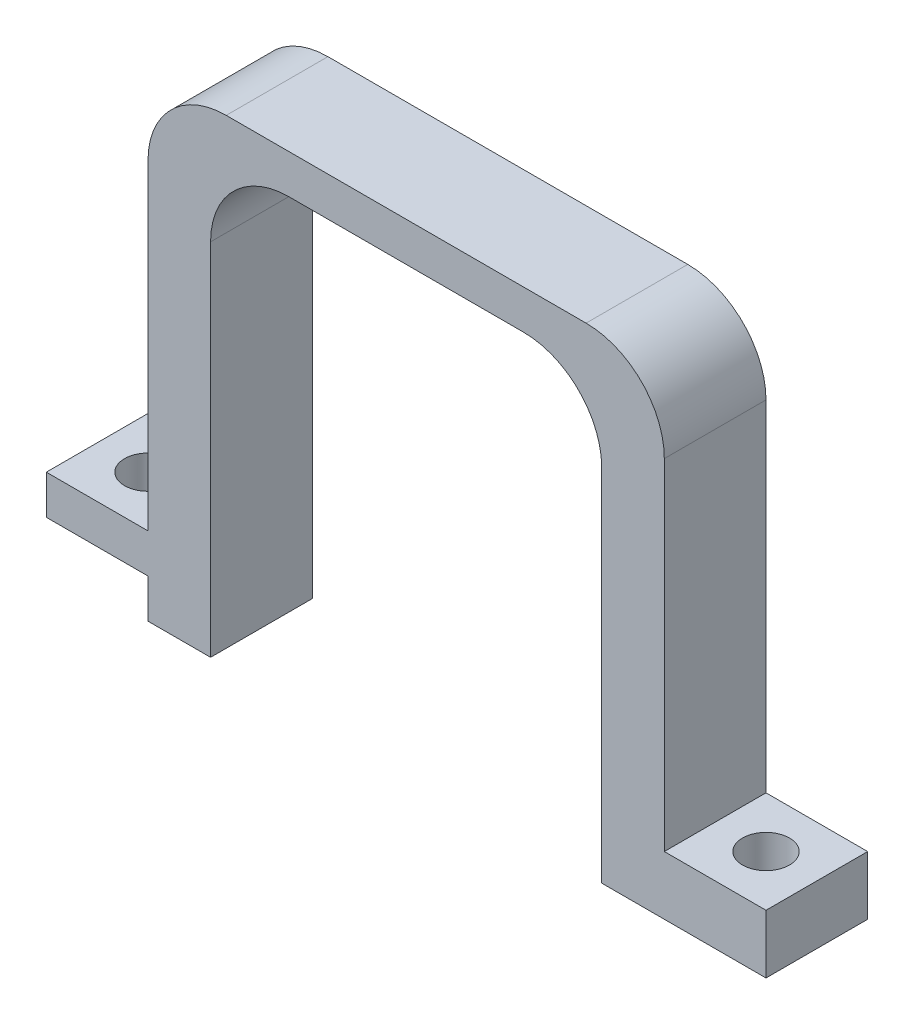
SolidWorks part; units mm, degrees
ref_plane "前视基准面" through (0, 0, 0) normal (0, 0, 1) x (1, 0, 0)
ref_plane "上视基准面" through (0, 0, 0) normal (0, 1, 0) x (1, 0, 0)
ref_plane "右视基准面" through (0, 0, 0) normal (1, 0, 0) x (0, 0, -1)
other "Configuration Table"
sketch "草图1" plane through (0, 0, 0) normal (0, 0, 1) x (1, 0, 0)
  line L1 (-6.6, 6.1) -> (6.6, 6.1)
  line L2 (-6.6, 6.1) -> (-6.6, -6.1)
  line L3 (-6.6, -6.1) -> (6.6, -6.1)
  line L4 (6.6, 6.1) -> (6.6, -6.1)
  line L9 (-5, 5.1) -> (5, 5.1)
  line L10 (-5, 5.1) -> (-5, -6.1)
  line L11 (-5, -6.1) -> (5, -6.1)
  line L12 (5, 5.1) -> (5, -6.1)
  point P5 (6.6, 0)
  point P7 (0, -6.1)
  point P11 (0, 5.1)
  dimension "D3" = 10
  dimension "D1" = 13.2
  dimension "D2" = 12.2
  dimension "D4" = 11.2
extrude "凸台-拉伸1" add sketch "草图1" along normal blind 2.6 contours L3 L4 L1 L2 | L10 L11 L12 L9
fillet "圆角1" radius 2 4 edges at (-6.6, 6.1, 1.3) (6.6, 6.1, 1.3) (-5, 5.1, 1.3) (5, 5.1, 1.3)
sketch "草图2" plane through (0, -6.1, 0) normal (0, -1, 0) x (1, 0, 0)
  line L0 (-6.6, 2.6) -> (-5, 2.6) construction
  line L1 (-6.6, 0) -> (-9.2, 0)
  line L2 (-6.6, 0) -> (-6.6, 2.6)
  line L3 (-6.6, 2.6) -> (-9.2, 2.6)
  line L4 (-9.2, 0) -> (-9.2, 2.6)
  line L5 (6.6, 0) -> (9.2, 0)
  line L6 (6.6, 0) -> (6.6, 2.6)
  line L7 (6.6, 2.6) -> (9.2, 2.6)
  line L8 (9.2, 0) -> (9.2, 2.6)
  line L9 (-6.6, 4.35) -> (-6.6, 2.6) construction
  circle A0 centre (-7.9, 1.3) radius 0.6
  circle A1 centre (7.9, 1.3) radius 0.6
  point P21 (7.9, 2.6)
  point P23 (9.2, 1.3)
  point P26 (-7.9, 2.6)
  line M6 (-6.6, 2.6) -> (-6.6, 0)
  dimension "D1" = 1.2
extrude "凸台-拉伸2" add sketch "草图2" against normal blind 2 contours L4 L1 L3 A0 M6 | L5 L8 L7 L6 A1
sketch "草图4" plane through (0, 0, 2.6) normal (0, 0, 1) x (1, 0, 0)
  line L1 (6.6, -4.1) -> (9.2, -4.1)
  line L2 (6.6, -4.1) -> (6.6, -4.6)
  line L3 (6.6, -4.6) -> (9.2, -4.6)
  line L4 (9.2, -4.1) -> (9.2, -4.6)
  line L5 (-6.6, 4.1) -> (-6.6, -4.1) construction
  line L6 (-9.2, -6.1) -> (-6.6, -6.1)
  line L7 (-9.2, -6.1) -> (-9.2, -5.1)
  line L8 (-9.2, -5.1) -> (-6.6, -5.1)
  line L9 (-6.6, -6.1) -> (-6.6, -5.1)
  line L10 (9.2, -4.1) -> (9.2, -6.1) construction
  point P12 (0, 0)
  line M7 (-9.2, -4.1) -> (-9.2, -6.1)
  line M8 (-9.2, -6.1) -> (-5, -6.1)
  dimension "D1" = 1
  dimension "D2" = 0.5
extrude "切除-拉伸1" cut sketch "草图4" against normal through all contours L9 L8 M8 M7 | L3 L4 L1 L2
